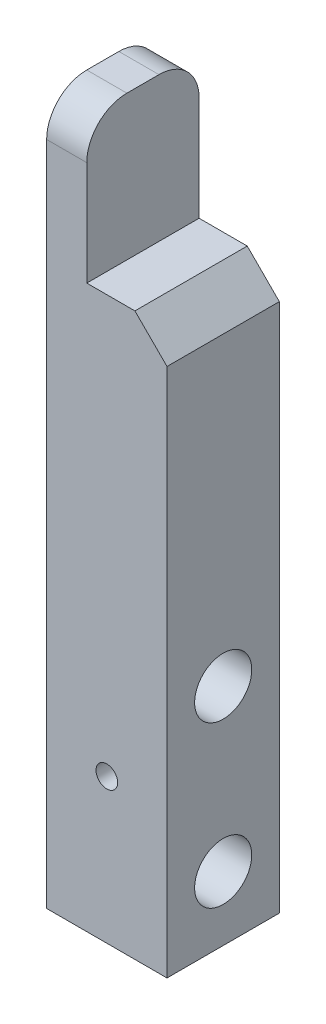
SolidWorks part; units mm, degrees
ref_plane "前视基准面" through (0, 0, 0) normal (0, 0, 1) x (1, 0, 0)
ref_plane "上视基准面" through (0, 0, 0) normal (0, 1, 0) x (1, 0, 0)
ref_plane "右视基准面" through (0, 0, 0) normal (1, 0, 0) x (0, 0, -1)
sketch "草图1" plane through (0, 0, 0) normal (0, 0, 1) x (1, 0, 0)
  line L1 (-7.5, -18) -> (7.5, -18)
  line L2 (-7.5, -18) -> (-7.5, 47)
  line L4 (7.5, -18) -> (7.5, 23)
  line L8 (-7.5, 47) -> (-7.5, 52)
  line L9 (-2.5, 52) -> (7.5, 52)
  line L10 (7.5, 23) -> (7.5, 52)
  line L12 (-7.5, 52) -> (-7.5, 70)
  line L13 (-7.5, 70) -> (-2.5, 70)
  line L14 (-2.5, 52) -> (-2.5, 70)
  point P0 (0, 0)
  dimension "D1" = 52
  dimension "D2" = 15
  dimension "D3" = 18
  dimension "D4" = 5
  dimension "D5" = 18
  dimension "D8" = 7.5
extrude "凸台-拉伸1" add sketch "草图1" along normal mid plane 14 contours L2 L8 L12 L13 L14 L9 L10 L4 L1
sketch "草图3" plane through (7.5, 0, 0) normal (1, 0, 0) x (0, 0, -1)
  circle A0 centre (0, -10) radius 3.56
  circle A1 centre (0, 10) radius 3.56
  dimension "D1" = 7.12
  dimension "D2" = 7.12
  dimension "D3" = 10
  dimension "D4" = 10
extrude "切除-拉伸1" cut sketch "草图3" against normal blind 20
sketch "草图4" plane through (0, 0, 7) normal (0, 0, 1) x (1, 0, 0)
  circle A0 centre (0, 0) radius 1.35
  dimension "D1" = 2.7
extrude "切除-拉伸2" cut sketch "草图4" against normal blind 14
fillet "圆角1" radius 5 2 edges at (-5, 70, -7) (-5, 70, 7)
chamfer "倒角1" distance 4 angle 45 1 edges at (7.5, 52, 0)
